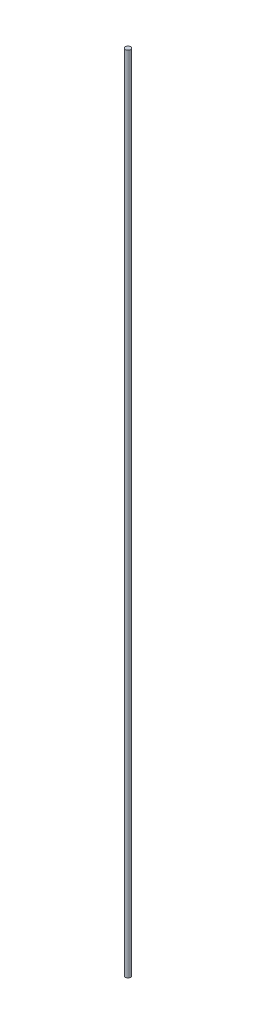
SolidWorks part; units mm, degrees
material "Custom Plastic"
ref_plane "Front Plane" through (0, 0, 0) normal (0, 0, 1) x (1, 0, 0)
ref_plane "Top Plane" through (0, 0, 0) normal (0, 1, 0) x (1, 0, 0)
ref_plane "Right Plane" through (0, 0, 0) normal (1, 0, 0) x (0, 0, -1)
sketch "Sketch1" plane through (0, 0, 0) normal (0, 1, 0) x (1, 0, 0)
  circle A0 centre (0, 0) radius 2
  dimension "D1" = 4
extrude "Boss-Extrude2" add sketch "Sketch1" along normal blind 622
cosmetic thread "Cosmetic Thread4" parameters "D2"=3.22
